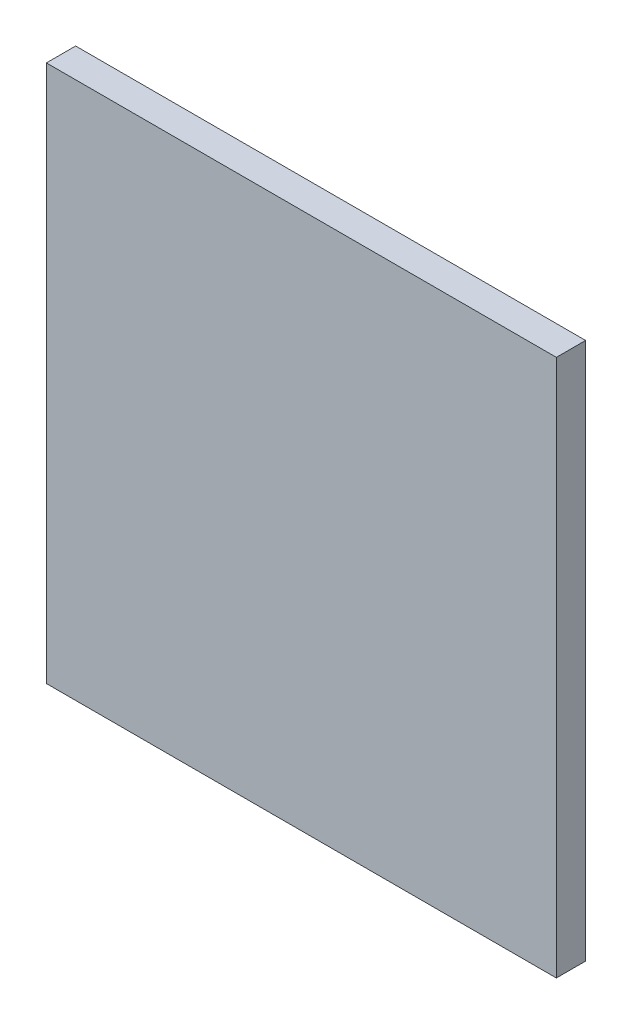
SolidWorks part; units mm, degrees
ref_plane "Front Plane" through (0, 0, 0) normal (0, 0, 1) x (1, 0, 0)
ref_plane "Top Plane" through (0, 0, 0) normal (0, 1, 0) x (1, 0, 0)
ref_plane "Right Plane" through (0, 0, 0) normal (1, 0, 0) x (0, 0, -1)
sketch "Sketch2" plane through (0, 0, 0) normal (0, 0, 1) x (1, 0, 0)
  line L1 (-77.2395, -17.5933) -> (254.8304, -17.5933)
  line L2 (-77.2395, -17.5933) -> (-77.2395, -367.5933)
  line L3 (-77.2395, -367.5933) -> (254.8304, -367.5933)
  line L4 (254.8304, -17.5933) -> (254.8304, -367.5933)
  dimension "D1" = 350
extrude "Boss-Extrude1" add sketch "Sketch2" along normal blind 19.05
sketch "Sketch3" plane through (0, 0, 19.05) normal (0, 0, 1) x (-1, 0, 0)
  line L0 (-254.8304, 367.5933) -> (-254.8304, 17.5933) construction
  circle A0 centre (-244.8304, 88.7832) radius 1.621
  circle A1 centre (-219.8304, 88.7832) radius 1.621
  circle A2 centre (-219.8304, 58.7832) radius 1.621
  circle A3 centre (-244.8304, 58.7832) radius 1.621
  circle A4 centre (-74.8304, 58.7832) radius 1.621
  circle A5 centre (-49.8304, 58.7832) radius 1.621
  circle A6 centre (-49.8304, 88.7832) radius 1.621
  circle A7 centre (-74.8304, 88.7832) radius 1.621
  point P2 (-160.3672, 162.3649)
  point P5 (-160.3672, 162.6418)
  point P8 (-160.3672, 192.8223)
  point P11 (0, 0)
  point P14 (0, 0)
  point P17 (0, 0)
  point P20 (0, 0)
  point P23 (0, 0)
  point P24 (0, 0)
  point P25 (-185.4205, 193.0992)
  point P26 (9.6328, 163.8417)
  point P27 (-160.1745, 163.9958)
  point P28 (9.8255, 194.0305)
  point P29 (-65.2876, 58.7832)
  point P32 (0, 0)
  point P35 (-244.8591, 82.6014)
  dimension "D1" = 25
  dimension "D2" = 30
  dimension "D3" = 170
  dimension "D4" = 25
  dimension "D5" = 10
